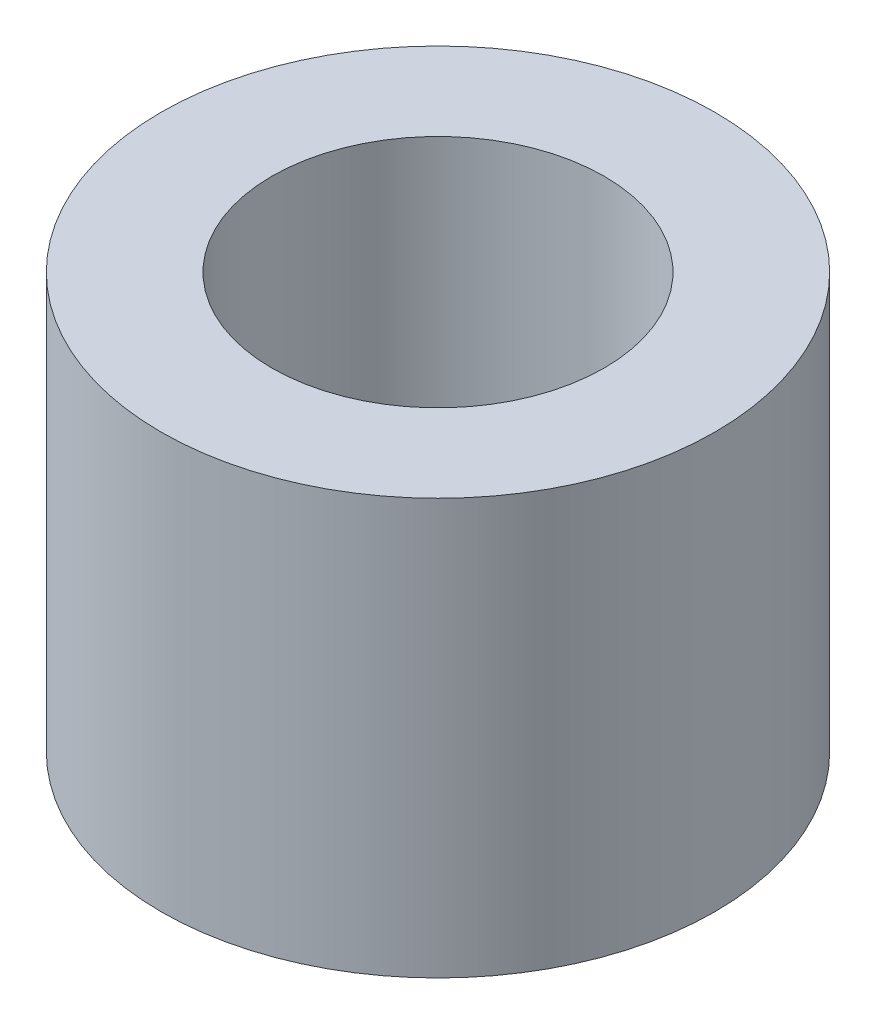
SolidWorks part; units mm, degrees
ref_plane "Front Plane" through (0, 0, 0) normal (0, 0, 1) x (1, 0, 0)
ref_plane "Top Plane" through (0, 0, 0) normal (0, 1, 0) x (1, 0, 0)
ref_plane "Right Plane" through (0, 0, 0) normal (1, 0, 0) x (0, 0, -1)
sketch "Sketch1" plane through (0, 0, 0) normal (0, 1, 0) x (1, 0, 0)
  circle A0 centre (0, 0) radius 2
  circle A1 centre (0, 0) radius 1.2
  dimension "D1" = 4
  dimension "D2" = 2.4
extrude "Boss-Extrude1" add sketch "Sketch1" along normal blind 3
